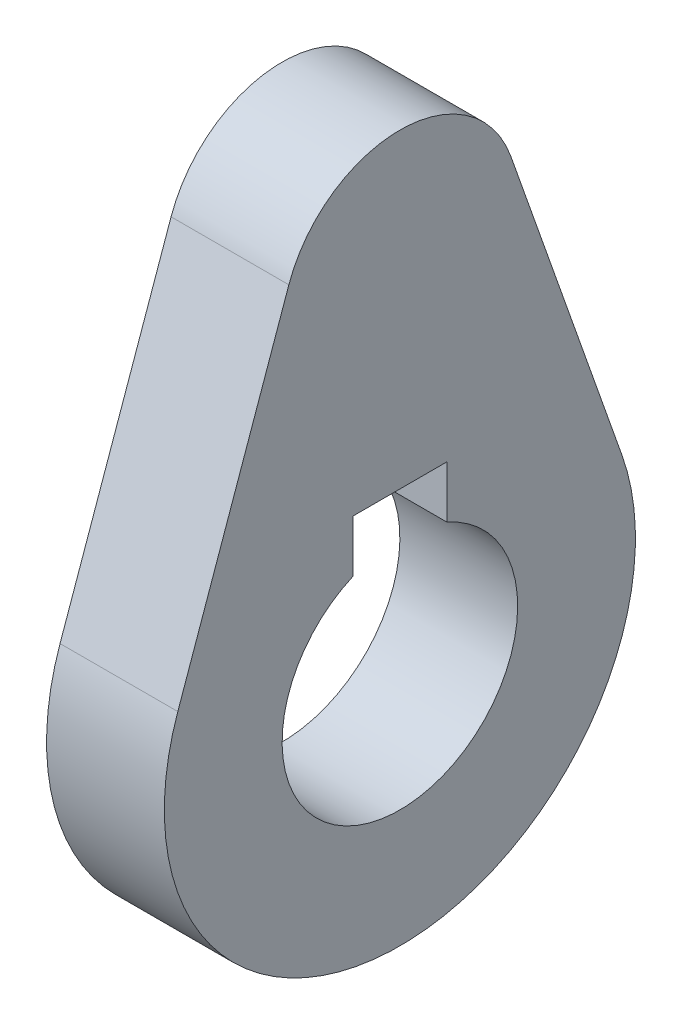
SolidWorks part; units mm, degrees
ref_plane "Front Plane" through (0, 0, 0) normal (0, 0, 1) x (1, 0, 0)
ref_plane "Top Plane" through (0, 0, 0) normal (0, 1, 0) x (1, 0, 0)
ref_plane "Right Plane" through (0, 0, 0) normal (1, 0, 0) x (0, 0, -1)
sketch "Sketch1" plane through (0, 0, 0) normal (1, 0, 0) x (0, 0, -1)
  line L0 (-4.714, 16.6667) -> (-9.4281, 3.3333)
  line L1 (4.714, 16.6667) -> (9.4281, 3.3333)
  line L3 (2, 0) -> (-2, 0)
  line L4 (2, 0) -> (2, 6.8021)
  line L5 (2, 6.8021) -> (-2, 6.8021)
  line L6 (-2, 0) -> (-2, 6.8021)
  circle A0 centre (0, 0) radius 10
  circle A1 centre (0, 15) radius 5
  circle A2 centre (0, 0) radius 5
  dimension "D1" = 10
  dimension "D5" = 10
  dimension "D6" = 15
  dimension "D7" = 20
  dimension "D2" = 7.09
  dimension "D3" = 7.09
  dimension "D4" = 4
extrude "Boss-Extrude1" add sketch "Sketch1" along normal blind 5 contours A1 A0 A2 L6 L5 L4 | A1 A0 L1 | A1 L0 A0 | A1 A0 | A0 A1
